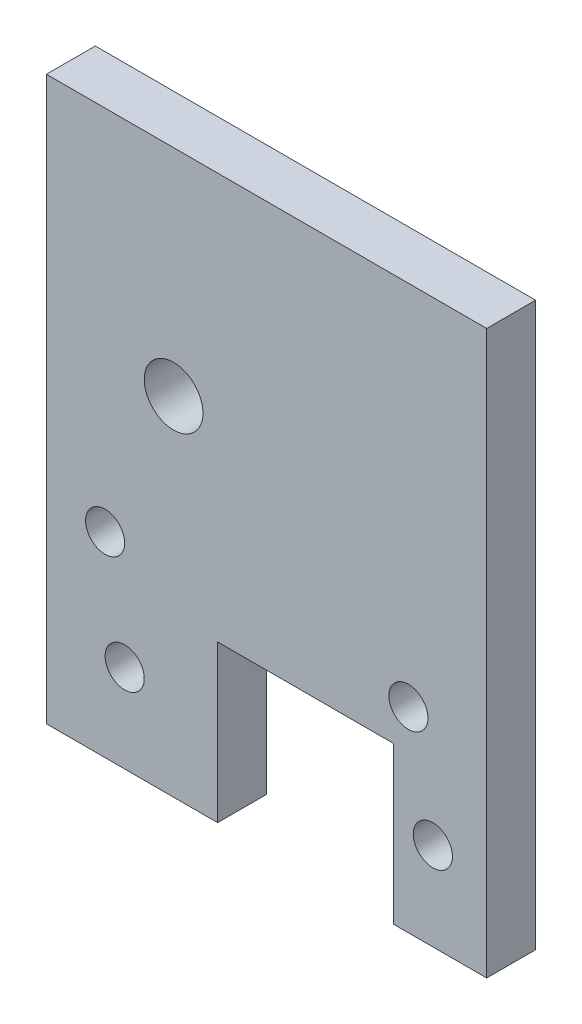
SolidWorks part; units mm, degrees
ref_plane "Front Plane" through (0, 0, 0) normal (0, 0, 1) x (1, 0, 0)
ref_plane "Top Plane" through (0, 0, 0) normal (0, 1, 0) x (1, 0, 0)
ref_plane "Right Plane" through (0, 0, 0) normal (1, 0, 0) x (0, 0, -1)
sketch "Sketch2" plane through (0, 0, 0) normal (0, 0, 1) x (1, 0, 0)
  line L0 (15.5, -17.75) -> (15.5, -26.75) construction
  line L1 (-21, 26.75) -> (21, 26.75) construction
  line L2 (-21, 26.75) -> (-21, -26.75) construction
  line L3 (-21, -26.75) -> (21, -26.75)
  line L4 (21, 26.75) -> (21, -26.75)
  line L5 (-21, 26.75) -> (21, -26.75) construction
  line L6 (-21, -26.75) -> (21, 26.75) construction
  line L7 (-63.8753, -19.107) -> (-103.8753, -19.107) construction
  line L8 (-63.8753, -19.107) -> (-63.8753, 20.893) construction
  line L9 (-63.8753, 20.893) -> (-103.8753, 20.893) construction
  line L10 (-103.8753, -19.107) -> (-103.8753, 20.893) construction
  line L11 (-63.8753, -19.107) -> (-103.8753, 20.893) construction
  line L12 (-63.8753, 20.893) -> (-103.8753, -19.107) construction
  line L13 (-11, 8.75) -> (-16, 8.75) construction
  line L17 (-7.5, -26.75) -> (7.5, -26.75)
  line L19 (15.5, -17.75) -> (15.5, -12.3835) construction
  line L20 (-5, -8.75) -> (10, -8.75) construction
  line L22 (-16, 8.75) -> (-16, -17.75) construction
  line L23 (-5, -8.75) -> (-5, -26.75) construction
  line L24 (-5, -26.75) -> (10, -26.75)
  line L25 (10, -8.75) -> (10, -26.75) construction
  line L26 (-5, -8.75) -> (10, -26.75) construction
  line L27 (-5, -26.75) -> (10, -8.75) construction
  line L28 (15.5, -12.3835) -> (10, -12.3835) construction
  line L29 (-21, 26.75) -> (-21, 30.75)
  line L30 (-6.5, -8.75) -> (11.5, -8.75) construction
  line L31 (-6.5, -8.75) -> (-6.5, -26.75)
  line L32 (-6.5, -26.75) -> (11.5, -26.75)
  line L33 (11.5, -8.75) -> (11.5, -26.75)
  line L34 (-6.5, -8.75) -> (11.5, -26.75) construction
  line L35 (-6.5, -26.75) -> (11.5, -8.75) construction
  line L36 (-21, 30.75) -> (21, 30.75)
  line L37 (21, 30.75) -> (21, 26.75)
  line L38 (-21, 30.75) -> (-24, 30.75)
  line L39 (-24, 30.75) -> (-24, -26.75)
  line L40 (-24, -26.75) -> (-21, -26.75)
  line L41 (-11, 8.75) -> (-11, -6.75) construction
  line L42 (-11, -6.75) -> (-16, -6.75) construction
  line L43 (-11, -6.75) -> (-18, -6.75) construction
  line L44 (-18, -6.75) -> (13, -6.75) construction
  line L45 (-6.5, -10.75) -> (11.5, -10.75)
  circle A0 centre (15.5, -17.75) radius 2
  circle A1 centre (-16, -17.75) radius 2
  circle A2 centre (-11, 8.75) radius 3
  circle A3 centre (-18, -6.75) radius 2
  circle A4 centre (13, -6.75) radius 2
  point P0 (0, 0)
  point P9 (-83.8753, 0.893)
  point P14 (2.5, -17.75)
  point P15 (0, -26.75)
  point P18 (2.5, -17.75)
  point P23 (0, -26.75)
  dimension "D3" = 4
  dimension "D8" = 4
  dimension "D11" = 6
  dimension "D20" = 4
  dimension "D22" = 4
  dimension "D1" = 53.5
  dimension "D2" = 42
  dimension "D4" = 40
  dimension "D5" = 40
  dimension "D6" = 9
  dimension "D7" = 31.5
  dimension "D9" = 15
  dimension "D10" = 18
  dimension "D12" = 26.5
  dimension "D13" = 5
  dimension "D14" = 5.5
  dimension "D15" = 18
  dimension "D16" = 4
  dimension "D17" = 3
  dimension "D18" = 15.5
  dimension "D19" = 7
  dimension "D21" = 31
  dimension "D23" = 2
extrude "Boss-Extrude1" add sketch "Sketch2" against normal blind 5
